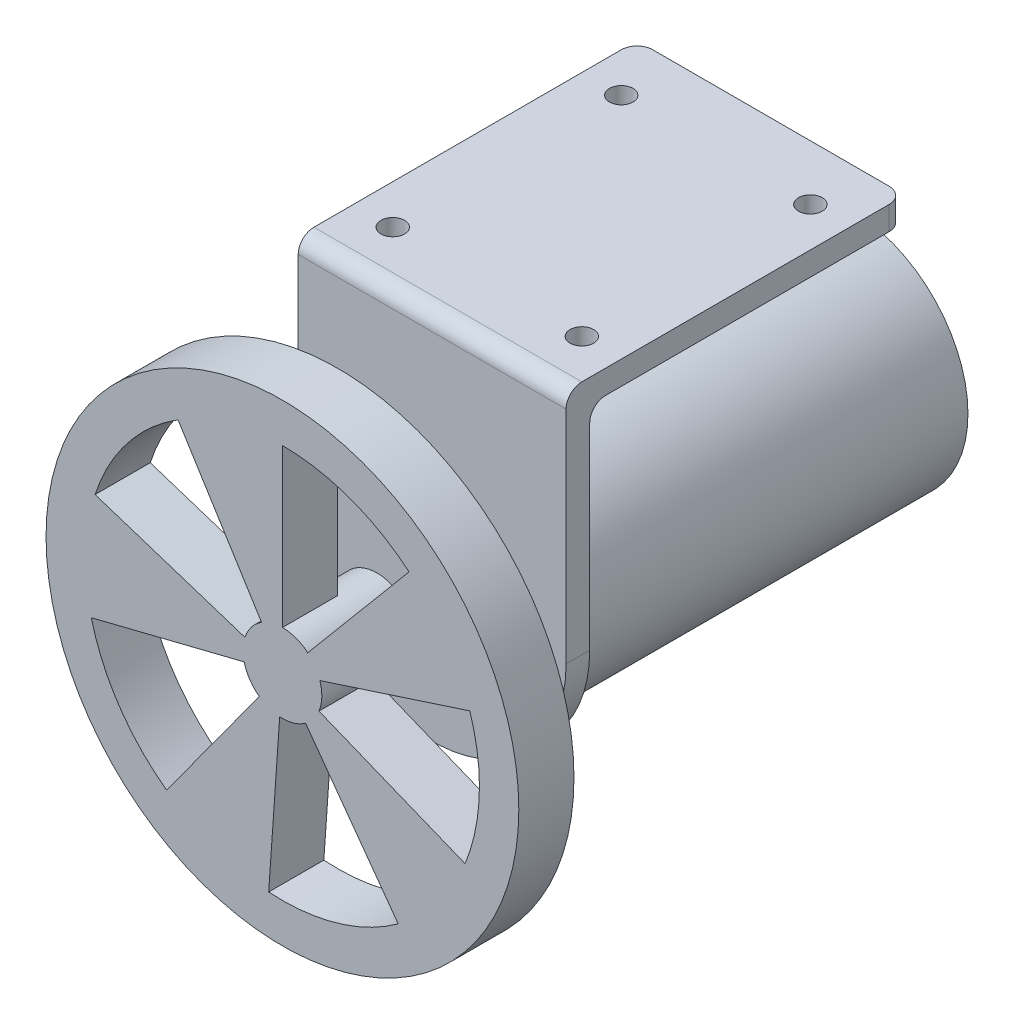
SolidWorks part; units mm, degrees
ref_plane "Front Plane" through (0, 0, 0) normal (0, 0, 1) x (1, 0, 0)
ref_plane "Top Plane" through (0, 0, 0) normal (0, 1, 0) x (1, 0, 0)
ref_plane "Right Plane" through (0, 0, 0) normal (1, 0, 0) x (0, 0, -1)
sketch "Sketch1" plane through (0, 0, 0) normal (0, 0, 1) x (1, 0, 0)
  circle A0 centre (0, 0) radius 15
  dimension "D1" = 30
extrude "Boss-Extrude1" add sketch "Sketch1" along normal blind 50
sketch "Sketch2" plane through (0, 0, 50) normal (0, 0, 1) x (1, 0, 0)
  circle A0 centre (0, 0) radius 1.5
  dimension "D1" = 3
extrude "Boss-Extrude2" add sketch "Sketch2" along normal blind 15
sketch "Sketch4" plane through (0, 0, 50) normal (0, 0, 1) x (1, 0, 0)
  line L0 (-17, 0) -> (-17, 30)
  line L1 (-17, 30) -> (17, 30)
  line L2 (17, 30) -> (17, 0)
  arc A0 (17, 0) -> (-17, 0) centre (0, 0) cw
  dimension "D1" = 17
  dimension "D2" = 30
extrude "Boss-Extrude4" add sketch "Sketch4" along normal blind 3
sketch "Sketch5" plane through (0, 0, 50) normal (0, 0, -1) x (-1, 0, 0)
  line L0 (17, 30) -> (17, 0) construction
  line L1 (-17, 30) -> (17, 30)
  line L2 (-17, 30) -> (-17, 27)
  line L3 (-17, 27) -> (17, 27)
  line L4 (17, 30) -> (17, 27)
  dimension "D1" = 3
extrude "Boss-Extrude5" add sketch "Sketch5" along normal blind 40
fillet "Fillet2" radius 2 4 edges at (-17, 28.5, 10) (17, 28.5, 10) (0, 27, 50) (0, 30, 53)
sketch "Sketch6" plane through (0, 0, 65) normal (0, 0, 1) x (1, 0, 0)
  circle A0 centre (0, 0) radius 30
  dimension "D1" = 60
extrude "Boss-Extrude6" add sketch "Sketch6" along normal blind 7
sketch "Sketch7" plane through (0, 0, 72) normal (0, 0, 1) x (1, 0, 0)
  line L0 (0, 25) -> (0, 5)
  line L1 (3.2139, 3.8302) -> (16.0697, 19.1511)
  line L2 (23.7764, 7.7254) -> (4.7553, 1.5451)
  line L3 (4.6359, -1.873) -> (23.1796, -9.3652)
  line L4 (14.6946, -20.2254) -> (2.9389, -4.0451)
  line L5 (-0.3488, -4.9878) -> (-1.7439, -24.9391)
  line L6 (-14.6946, -20.2254) -> (-2.9389, -4.0451)
  line L7 (-4.8515, -1.2096) -> (-24.2574, -6.048)
  line L8 (-23.7764, 7.7254) -> (-4.7553, 1.5451)
  line L9 (-2.6496, 4.2402) -> (-13.248, 21.2012)
  arc A0 (0, 25) -> (16.0697, 19.1511) centre (0, 0) cw
  arc A1 (0, 5) -> (3.2139, 3.8302) centre (0, 0) cw
  arc A2 (23.7764, 7.7254) -> (23.1796, -9.3652) centre (0, 0) cw
  arc A3 (4.7553, 1.5451) -> (4.6359, -1.873) centre (0, 0) cw
  arc A4 (14.6946, -20.2254) -> (-1.7439, -24.9391) centre (0, 0) cw
  arc A5 (2.9389, -4.0451) -> (-0.3488, -4.9878) centre (0, 0) cw
  arc A6 (-14.6946, -20.2254) -> (-24.2574, -6.048) centre (0, 0) cw
  arc A7 (-2.9389, -4.0451) -> (-4.8515, -1.2096) centre (0, 0) cw
  arc A8 (-23.7764, 7.7254) -> (-13.248, 21.2012) centre (0, 0) cw
  arc A9 (-4.7553, 1.5451) -> (-2.6496, 4.2402) centre (0, 0) cw
  point P24 (0, 0)
  dimension "D1" = 25
  dimension "D4" = 5
  dimension "D2" = 25
  dimension "D3" = 25
  dimension "D5" = 40
  dimension "D6" = 20
  dimension "D7" = 20
  dimension "D8" = 5
extrude "Cut-Extrude1" cut sketch "Sketch7" against normal blind 7
sketch "Sketch8" plane through (0, 0, 65) normal (0, 0, -1) x (-1, 0, 0)
  circle A0 centre (0, 0) radius 5
  dimension "D1" = 10
extrude "Boss-Extrude7" add sketch "Sketch8" along normal blind 5
sketch "Sketch9" plane through (0, 30, 0) normal (0, 1, 0) x (1, 0, 0)
  line L0 (-17, -51) -> (-17, -12) construction
  line L1 (-17, -51) -> (17, -51) construction
  line L2 (0, -10) -> (0, -51) construction
  line L3 (-15, -10) -> (15, -10) construction
  line L4 (17, -31.5) -> (-17, -31.5) construction
  line L5 (17, -51) -> (17, -12) construction
  circle A0 centre (-12, -46) radius 1.5
  circle A1 centre (-12, -17) radius 1.5
  circle A2 centre (12, -46) radius 1.5
  circle A3 centre (12, -17) radius 1.5
  dimension "D1" = 3
  dimension "D2" = 5
  dimension "D3" = 5
extrude "Cut-Extrude2" cut sketch "Sketch9" against normal blind 5
